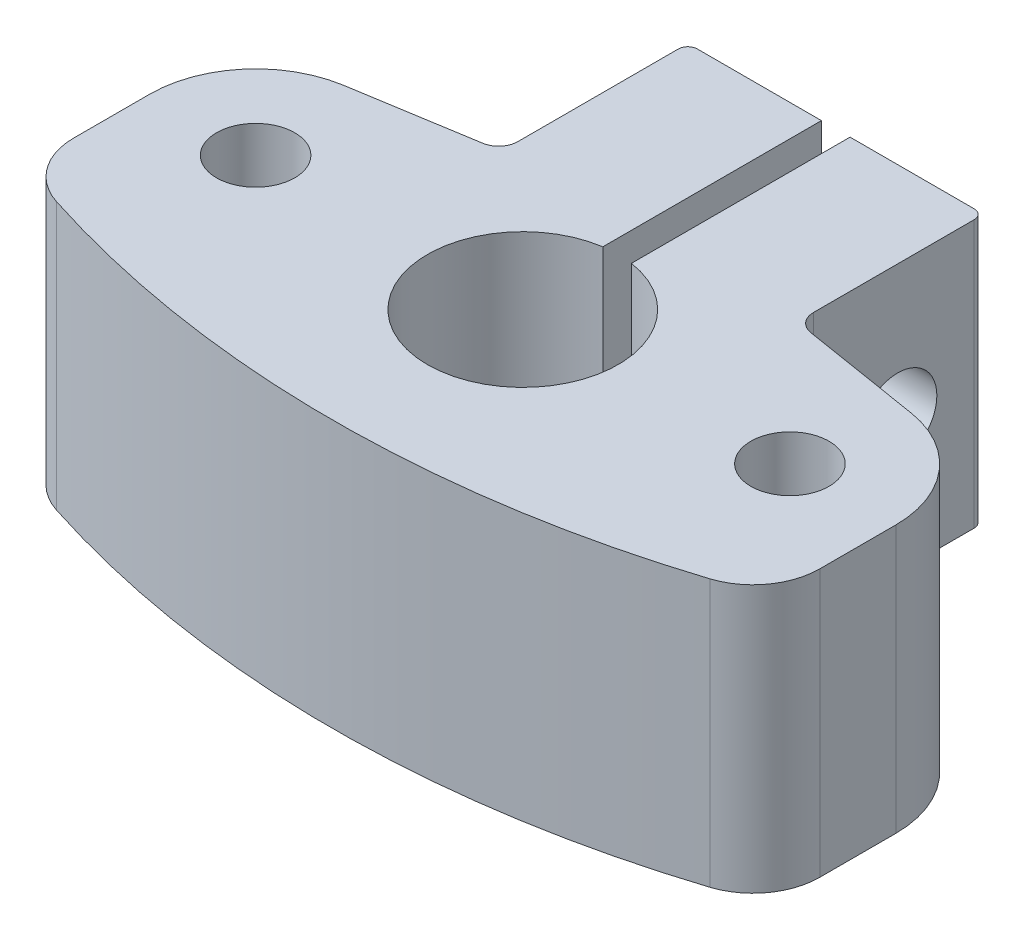
SolidWorks part; units mm, degrees
material "PLA+"
ref_plane "Front Plane" through (0, 0, 0) normal (0, 0, 1) x (1, 0, 0)
ref_plane "Top Plane" through (0, 0, 0) normal (0, 1, 0) x (1, 0, 0)
ref_plane "Right Plane" through (0, 0, 0) normal (1, 0, 0) x (0, 0, -1)
sketch "Sketch1" plane through (0, 0, 0) normal (0, 1, 0) x (1, 0, 0)
  line L0 (-19.55, 0) -> (-19.55, -3.9865)
  line L1 (19.55, 0) -> (19.55, -3.9865)
  line L2 (0, 0) -> (0, 16.4) construction
  line L3 (0.75, 4.9434) -> (0.75, 16.4)
  line L4 (-0.75, 4.9434) -> (-0.75, 16.4)
  line L5 (-7.25, 16.4) -> (-0.75, 16.4)
  line L6 (7.75, 7.4871) -> (7.75, 15.9)
  line L7 (-7.75, 7.4871) -> (-7.75, 15.9)
  line L8 (7.75, 0) -> (7.75, 16.6498) construction
  line L9 (-7.75, 0) -> (-7.75, 16.6498) construction
  line L10 (-14.8886, 5.4784) -> (-8.5899, 6.5)
  line L11 (14.8886, 5.4784) -> (8.5899, 6.5)
  line L12 (0, 0) -> (0, 16.6498) construction
  line L13 (-0.75, 0) -> (-0.75, 16.6498) construction
  line L14 (0.75, 0) -> (0.75, 16.6498) construction
  line L15 (0.75, 16.4) -> (7.25, 16.4)
  arc A0 (-0.75, 4.9434) -> (0.75, 4.9434) centre (0, 0) ccw
  circle A1 centre (-14, 0) radius 2.05
  circle A2 centre (14, 0) radius 2.05
  arc A3 (-14.8886, 5.4784) -> (-19.55, 0) centre (-14, 0) ccw
  arc A4 (19.55, 0) -> (14.8886, 5.4784) centre (14, 0) ccw
  arc A5 (-17.12, -7.3189) -> (17.12, -7.3189) centre (0, 46) ccw
  arc A6 (7.75, 7.4871) -> (8.5899, 6.5) centre (8.75, 7.4871) ccw
  arc A7 (-7.75, 7.4871) -> (-8.5899, 6.5) centre (-8.75, 7.4871) cw
  arc A8 (7.75, 15.9) -> (7.25, 16.4) centre (7.25, 15.9) ccw
  arc A9 (-7.25, 16.4) -> (-7.75, 15.9) centre (-7.25, 15.9) ccw
  arc A10 (19.55, -3.9865) -> (17.12, -7.3189) centre (16.05, -3.9865) cw
  arc A11 (-19.55, -3.9865) -> (-17.12, -7.3189) centre (-16.05, -3.9865) ccw
  circle A12 centre (-14, 0) radius 5.55 construction
  circle A13 centre (14, 0) radius 5.55 construction
  dimension "D1" = 4.1
  dimension "D2" = 4.1
  dimension "D3" = 10
  dimension "D7" = 112
  dimension "D14" = 1
  dimension "D16" = 0.5
  dimension "D18" = 3.5
  dimension "D4" = 14
  dimension "D5" = 14
  dimension "D8" = 46
  dimension "D11" = 16.4
  dimension "D15" = 6.5
  dimension "D17" = 6.5
  dimension "D6" = 3.5
  dimension "D9" = 0.75
  dimension "D10" = 0.75
  dimension "D12" = 7
  dimension "D13" = 7
extrude "Boss-Extrude1" add sketch "Sketch1" along normal blind 14
sketch "Sketch2" plane through (7.75, 0, 0) normal (1, 0, 0) x (0, 0, -1)
  line L0 (16.4, 14) -> (16.4, 0) construction
  line L1 (7.4871, 14) -> (15.9, 14) construction
  circle A0 centre (11.9, 7) radius 2.05
  dimension "D1" = 4.5
  dimension "D3" = 4.1
  dimension "D2" = 7
extrude "Cut-Extrude1" cut sketch "Sketch2" against normal through all
